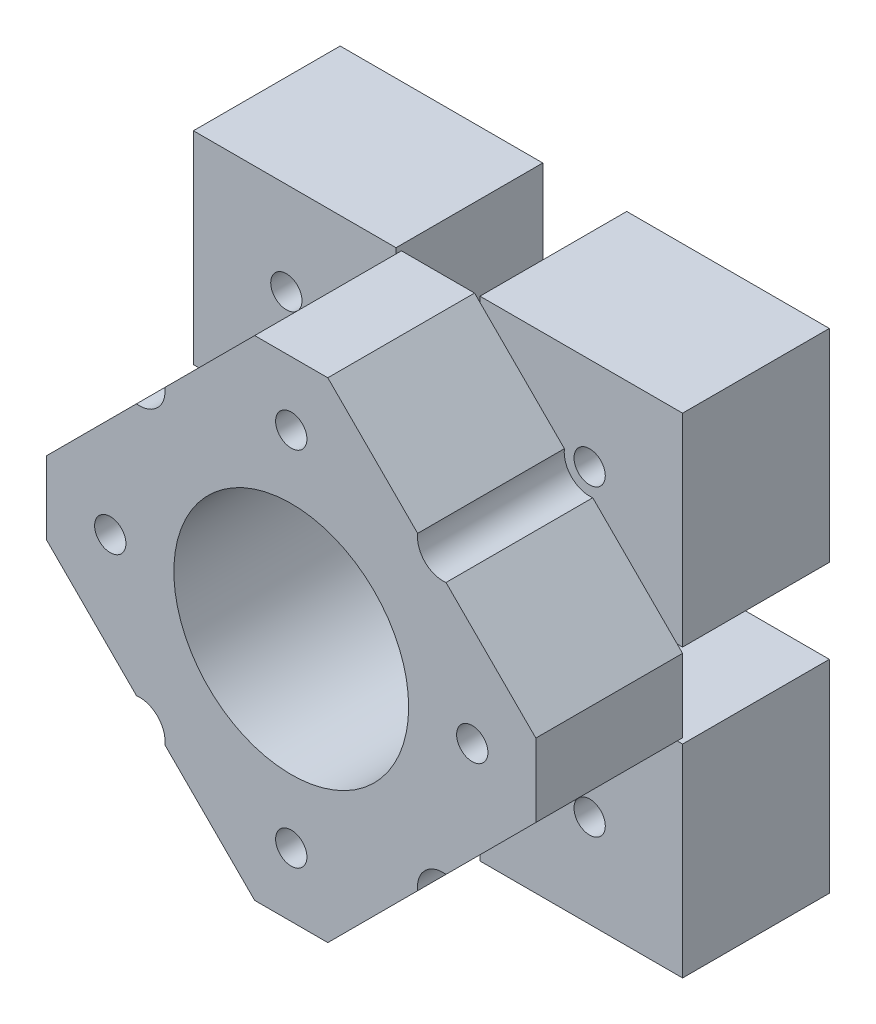
SolidWorks part; units mm, degrees
ref_plane "前视基准面" through (0, 0, 0) normal (0, 0, 1) x (1, 0, 0)
ref_plane "上视基准面" through (0, 0, 0) normal (0, 1, 0) x (1, 0, 0)
ref_plane "右视基准面" through (0, 0, 0) normal (1, 0, 0) x (0, 0, -1)
other "Configuration Table"
sketch "草图1" plane through (0, 0, 0) normal (0, 0, 1) x (1, 0, 0)
  line L1 (-25, -25) -> (25, -25)
  line L2 (-25, -25) -> (-25, 25)
  line L3 (-25, 25) -> (25, 25)
  line L4 (25, -25) -> (25, 25)
  line L5 (-25, -25) -> (25, 25) construction
  line L6 (-25, 25) -> (25, -25) construction
  point P0 (0, 0)
  dimension "D1" = 50
  dimension "D2" = 50
extrude "凸台-拉伸1" add sketch "草图1" along normal blind 30
hole_wizard "中间大孔" positions "草图2" profile "草图3" legacy end condition through all
sketch "草图2" plane through (0, 0, 30) normal (0, 0, 1) x (1, 0, 0)
  point P0 (0, 0)
sketch "草图3" plane through (0, 0, 30) normal (1, 0, 0) x (0, -1, 0)
  line L0 (0, 0) -> (0, 30)
  line L1 (0, 30) -> (12, 30)
  line L2 (12, 30) -> (12, 0)
  line L3 (12, 0) -> (0, 0)
  line L4 (0, 110) -> (0, -10) construction
  dimension "直径" = 24
  dimension "深度" = 30
sketch "草图6" plane through (0, 0, 30) normal (0, 0, 1) x (1, 0, 0)
  line L0 (0, 0) -> (25, 0) construction
  line L2 (0, 0) -> (0, 25) construction
sketch "草图7" plane through (0, 0, 30) normal (0, 0, 1) x (1, 0, 0)
  line L1 (-15.5, -15.5) -> (15.5, -15.5)
  line L2 (-15.5, -15.5) -> (-15.5, 15.5)
  line L3 (-15.5, 15.5) -> (15.5, 15.5)
  line L4 (15.5, -15.5) -> (15.5, 15.5)
  line L5 (-15.5, -15.5) -> (15.5, 15.5) construction
  line L6 (-15.5, 15.5) -> (15.5, -15.5) construction
  circle A0 centre (0, 0) radius 18.5
  point P0 (0, 0)
  dimension "D3" = 21.9203
  dimension "D4" = 37
  dimension "D1" = 31
  dimension "D2" = 31
hole_wizard "孔1" positions "草图8" profile "草图9" legacy end condition through all
sketch "草图8" plane through (0, 0, 30) normal (0, 0, 1) x (1, 0, 0)
  point P0 (-15.5, 15.5)
  point P3 (15.5, 15.5)
  point P6 (15.5, -15.5)
  point P9 (-15.5, -15.5)
sketch "草图9" plane through (-15.5, 15.5, 30) normal (1, 0, 0) x (0, -1, 0)
  line L0 (0, 0) -> (0, 30)
  line L1 (0, 30) -> (1.6, 30)
  line L2 (1.6, 30) -> (1.6, 0)
  line L3 (1.6, 0) -> (0, 0)
  line L4 (0, 110) -> (0, -10) construction
  dimension "直径" = 3.2
  dimension "深度" = 30
hole_wizard "孔2" positions "草图11" profile "草图12" legacy end condition through all
sketch "草图11" plane through (0, 0, 30) normal (0, 0, 1) x (1, 0, 0)
  line L0 (0, -200000) -> (0, 200025) construction
  line L1 (-200000, 0) -> (200025, 0) construction
  circle A0 centre (0, 0) radius 18.5 construction
  point P0 (0, 18.5)
  point P6 (18.5, 0)
  point P10 (0, -18.5)
  point P12 (-18.5, 0)
sketch "草图12" plane through (0, 18.5, 30) normal (1, 0, 0) x (0, -1, 0)
  line L0 (0, 0) -> (0, 30)
  line L1 (0, 30) -> (1.6, 30)
  line L2 (1.6, 30) -> (1.6, 0)
  line L3 (1.6, 0) -> (0, 0)
  line L4 (0, 110) -> (0, -10) construction
  dimension "直径" = 3.2
  dimension "深度" = 30
sketch "草图13" plane through (0, 0, 30) normal (0, 0, 1) x (1, 0, 0)
  line L0 (-14.3686, 14.3686) -> (-3.7373, 25)
  line L1 (-15.5, 15.5) -> (15.5, -15.5) construction
  line L2 (25, 25) -> (-25, 25) construction
  line L3 (-14.3686, 14.3686) -> (-25, 3.7373)
  line L4 (-25, 25) -> (-25, -25) construction
  line L8 (14.3686, 14.3686) -> (25, 3.7373)
  line L9 (14.3686, 14.3686) -> (3.7373, 25)
  line L11 (-14.3686, -14.3686) -> (-25, -3.7373)
  line L12 (-14.3686, -14.3686) -> (-3.7373, -25)
  line L13 (14.3686, -14.3686) -> (3.7373, -25)
  line L14 (14.3686, -14.3686) -> (25, -3.7373)
  circle A0 centre (-15.5, 15.5) radius 1.6 construction
ref_plane "基准面1" through (0, 0, 15) normal (0, 0, -1) x (-1, 0, 0)
extrude "切除-拉伸-薄壁1" cut sketch "草图13" along direction (0, 0, -1) on the side against the normal blind 15 thin thin type one direction wall 20
sketch "草图16" plane through (0, 0, 0) normal (0, 0, -1) x (-1, 0, 0)
  line L0 (-25, 25) -> (25, 25) construction
  line L2 (-4.2901, 15.5) -> (-4.2901, 25)
  line L3 (-4.2901, 25) -> (4.2901, 25)
  line L4 (4.2901, 15.5) -> (4.2901, 25)
  line L5 (-1.98, 15.5) -> (4.2901, 25) construction
  line L6 (-4.2901, 25) -> (1.98, 15.5) construction
  line L7 (15.5, 15.5) -> (-15.5, 15.5) construction
  line L8 (-4.2901, 15.5) -> (4.2901, 15.5)
  line L14 (-4.2901, -15.5) -> (4.2901, -15.5)
  line L15 (4.2901, -15.5) -> (4.2901, -25)
  line L16 (-4.2901, -25) -> (4.2901, -25)
  line L17 (-4.2901, -15.5) -> (-4.2901, -25)
  line L18 (-15.5, -4.2901) -> (-25, -4.2901)
  line L19 (-25, -4.2901) -> (-25, 4.2901)
  line L20 (-15.5, 4.2901) -> (-25, 4.2901)
  line L21 (-15.5, -4.2901) -> (-15.5, 4.2901)
  line L22 (15.5, -4.2901) -> (15.5, 4.2901)
  line L23 (15.5, 4.2901) -> (25, 4.2901)
  line L24 (25, -4.2901) -> (25, 4.2901)
  line L25 (15.5, -4.2901) -> (25, -4.2901)
  point P0 (0, 18.5)
  dimension "D1" = 0
extrude "切除-拉伸3" cut sketch "草图16" against normal blind 15
hole_wizard "孔3" positions "草图17" profile "草图18" legacy
sketch "草图17" plane through (0, 0, 30) normal (0, 0, 1) x (1, 0, 0)
  point P0 (-15.5, 15.5)
  point P3 (15.5, 15.5)
  point P6 (15.5, -15.5)
  point P9 (-15.5, -15.5)
sketch "草图18" plane through (-15.5, 15.5, 30) normal (1, 0, 0) x (0, -1, 0)
  line L0 (0, 0) -> (0, 15)
  line L1 (0, 15) -> (2.6, 15)
  line L2 (2.6, 15) -> (2.6, 0)
  line L3 (2.6, 0) -> (0, 0)
  line L4 (0, 110) -> (0, -10) construction
  dimension "直径" = 5.2
  dimension "深度" = 15
